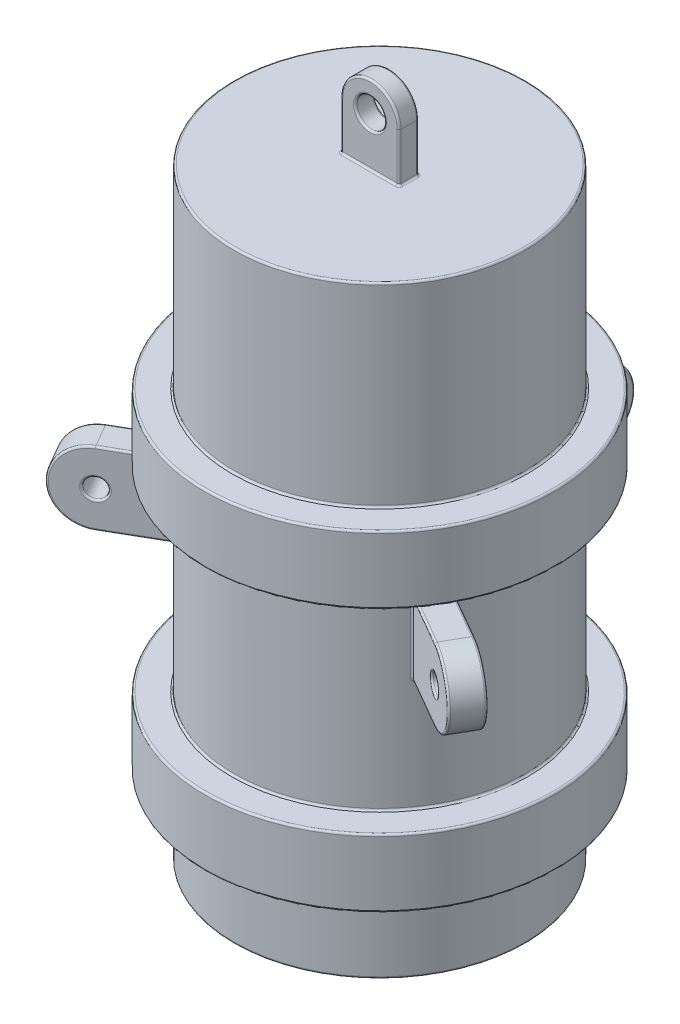
SolidWorks part; units mm, degrees
ref_plane "Front Plane" through (0, 0, 0) normal (0, 0, 1) x (1, 0, 0)
ref_plane "Top Plane" through (0, 0, 0) normal (0, 1, 0) x (1, 0, 0)
ref_plane "Right Plane" through (0, 0, 0) normal (1, 0, 0) x (0, 0, -1)
sketch "Sketch1" plane through (0, 0, 0) normal (0, 0, 1) x (1, 0, 0)
  line L0 (0, 0) -> (0, 62) construction
  line L1 (-4, 0) -> (-15, 0)
  line L2 (-15, 0) -> (-15, 8)
  line L3 (-15, 8) -> (-18, 8)
  line L4 (-18, 8) -> (-18, 15)
  line L5 (-18, 15) -> (-15, 15)
  line L6 (-15, 15) -> (-15, 35)
  line L7 (-15, 35) -> (-18, 35)
  line L8 (-18, 35) -> (-18, 42)
  line L9 (-18, 42) -> (-15, 42)
  line L10 (-15, 42) -> (-15, 62)
  line L11 (-15, 62) -> (0, 62)
  line L12 (-4, 1) -> (-14, 1)
  line L13 (-14, 1) -> (-14, 9)
  line L14 (-14, 9) -> (-17, 9)
  line L15 (-17, 9) -> (-17, 14)
  line L16 (-17, 14) -> (-14, 14)
  line L17 (-14, 14) -> (-14, 36)
  line L18 (-14, 36) -> (-17, 36)
  line L19 (-17, 36) -> (-17, 41)
  line L20 (-17, 41) -> (-14, 41)
  line L21 (-14, 41) -> (-14, 61)
  line L22 (-14, 61) -> (0, 61)
  line L23 (0, 62) -> (0, 61)
  line L24 (-4, 1) -> (-4, 0)
  dimension "D1" = 4
  dimension "D2" = 11
  dimension "D3" = 8
  dimension "D4" = 7
  dimension "D5" = 20
  dimension "D6" = 20
  dimension "D7" = 3
  dimension "D8" = 7
  dimension "D9" = 1
revolve "Revolve1" add sketch "Sketch1" angle 360 about L0
sketch "Sketch2" plane through (0, 0, 0) normal (0, 0, 1) x (1, 0, 0)
  line L0 (15, 62) -> (-15, 62) construction
  line L1 (-3, 62) -> (3, 62)
  line L2 (-3, 62) -> (-3, 67)
  line L3 (-3, 67) -> (3, 67) construction
  line L4 (3, 67) -> (3, 62)
  circle A0 centre (0, 67) radius 1.5
  arc A1 (-3, 67) -> (3, 67) centre (0, 67) cw
  point P6 (0, 62)
  dimension "D1" = 3
  dimension "D3" = 1.5
  dimension "D2" = 5
extrude "Boss-Extrude1" add sketch "Sketch2" along normal mid plane 2
sketch "Sketch3" plane through (0, 0, 0) normal (1, 0, 0) x (0, 0, -1)
  line L0 (14, 34) -> (21, 34)
  line L1 (14, 14) -> (14, 36) construction
  line L2 (21, 34) -> (21, 26.5) construction
  line L3 (21, 26.5) -> (14, 26.5)
  line L4 (14, 26.5) -> (14, 34)
  line L5 (-18, 35) -> (18, 35) construction
  circle A0 centre (21, 30.25) radius 1
  arc A1 (21, 34) -> (21, 26.5) centre (21, 30.25) cw
  dimension "D3" = 2
  dimension "D1" = 7
  dimension "D2" = 1
  dimension "D4" = 7.5
extrude "Boss-Extrude2" add sketch "Sketch3" along normal mid plane 3
pattern_circular "CirPattern1" count 3 over 360 about axis through (0, 0, 0) along (0, 1, 0) of "Boss-Extrude2"
fillet "Fillet1" radius 0.2 70 edges at (0, 42, -15) (0, 42, -18) (0, 35, -18) (0, 15, -18) (0, 8, -18) (0, 8, -15) (0, 0, -15) (0, 0, -4) (0, 1, -4) (0, 1, -14) (0, 9, -14) (0, 9, -17) (0, 14, -17) (0, 14, -14) (0, 36, -14) (0, 36, -17) (0, 41, -17) (0, 41, -14) (0, 61, -14) (0, 62, -15) (0, 15, -15) (0, 35, -15) (12.1753, 30.25, 8.7614) (13.6753, 30.25, 6.1634) (16.3059, 26.5, 7.6822) (12.9904, 26.5, 7.5) (14.8059, 26.5, 10.2802) (14.8059, 34, 10.2802) (12.9904, 34, 7.5) (16.3059, 34, 7.6822) (20.6841, 30.25, 13.674) (22.1841, 30.25, 11.076) (19.8026, 30.25, 9.701) (18.3026, 30.25, 12.299) (-13.6753, 30.25, 6.1634) (-12.1753, 30.25, 8.7614) (-14.8059, 26.5, 10.2802) (-12.9904, 26.5, 7.5) (-16.3059, 26.5, 7.6822) (-16.3059, 34, 7.6822) (-12.9904, 34, 7.5) (-14.8059, 34, 10.2802) (-22.1841, 30.25, 11.076) (-20.6841, 30.25, 13.674) (-18.3026, 30.25, 12.299) (-19.8026, 30.25, 9.701) (1.5, 30.25, -14.9248) (-1.5, 30.25, -14.9248) (-1.5, 26.5, -17.9624) (0, 26.5, -15) (1.5, 26.5, -17.9624) (1.5, 34, -17.9624) (0, 34, -15) (-1.5, 34, -17.9624) (1.5, 30.25, -24.75) (-1.5, 30.25, -24.75) (-1.5, 30.25, -22) (1.5, 30.25, -22) (0, 62, 1) (0, 62, -1) (-3, 64.5, 1) (-3, 62, 0) (-3, 64.5, -1) (3, 62, 0) (3, 64.5, 1) (3, 64.5, -1) (0, 70, 1) (0, 70, -1) (1.5, 67, -1) (1.5, 67, 1)
